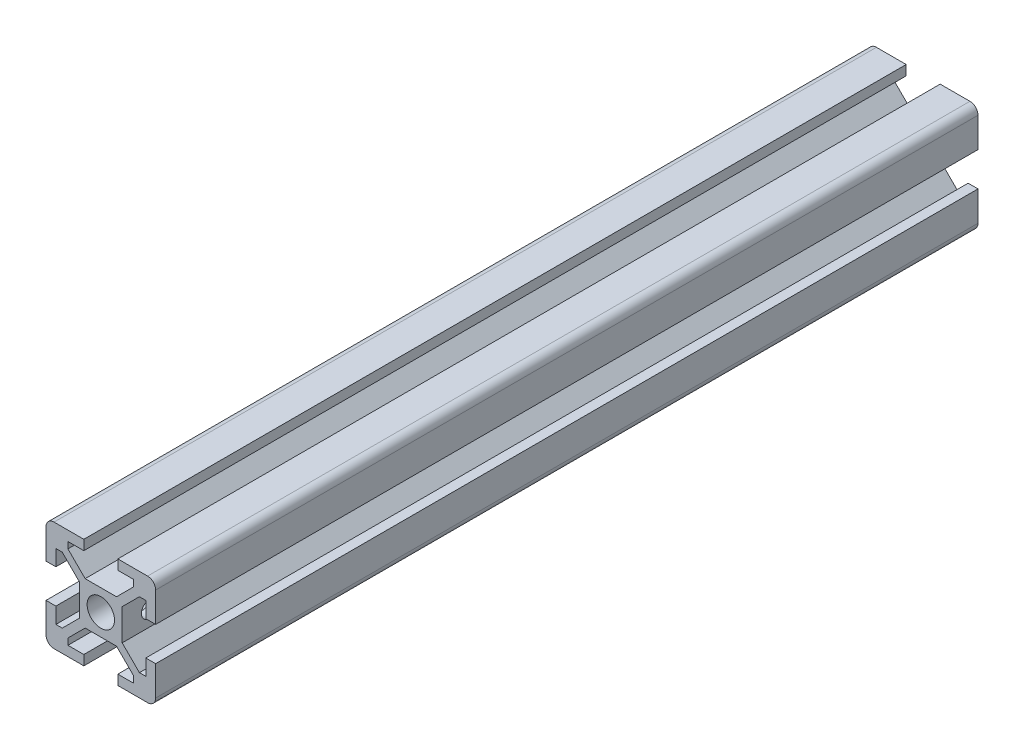
SolidWorks part; units mm, degrees
ref_plane "Front Plane" through (0, 0, 0) normal (0, 0, 1) x (1, 0, 0)
ref_plane "Top Plane" through (0, 0, 0) normal (0, 1, 0) x (1, 0, 0)
ref_plane "Right Plane" through (0, 0, 0) normal (1, 0, 0) x (0, 0, -1)
sketch "Sketch1" plane through (0, 0, 0) normal (0, 0, 1) x (1, 0, 0)
  line L0 (2.8606, 3.9) -> (6, 7.0394)
  line L5 (0, 3.9) -> (2.8606, 3.9)
  line L8 (3.9, 2.8606) -> (3.9, 0)
  line L9 (3.9, 0) -> (3.9, -2.8606)
  line L10 (3.9, -2.8606) -> (7.0394, -6)
  line L11 (6, 7.0394) -> (6, 8.2)
  line L12 (6, 8.2) -> (3.1, 8.2)
  line L13 (3.1, 8.2) -> (3.1, 10)
  line L14 (3.1, 10) -> (10, 10)
  line L15 (10, 10) -> (10, 3.1)
  line L16 (10, 3.1) -> (8.2, 3.1)
  line L17 (8.2, 3.1) -> (8.2, 6)
  line L18 (8.2, 6) -> (7.0394, 6)
  line L19 (7.0394, 6) -> (3.9, 2.8606)
  line L22 (7.0394, -6) -> (8.2, -6)
  line L23 (8.2, -6) -> (8.2, -3.1)
  line L24 (8.2, -3.1) -> (10, -3.1)
  line L25 (10, -3.1) -> (10, -10)
  line L26 (10, -10) -> (3.1, -10)
  line L27 (3.1, -10) -> (3.1, -8.2)
  line L28 (3.1, -8.2) -> (6, -8.2)
  line L29 (6, -8.2) -> (6, -7.0394)
  line L30 (6, -7.0394) -> (2.8606, -3.9)
  line L31 (2.8606, -3.9) -> (0, -3.9)
  line L32 (0, -3.9) -> (-2.8606, -3.9)
  line L33 (-2.8606, -3.9) -> (-6, -7.0394)
  line L34 (-6, -7.0394) -> (-6, -8.2)
  line L35 (-6, -8.2) -> (-3.1, -8.2)
  line L36 (-3.1, -8.2) -> (-3.1, -10)
  line L37 (-3.1, -10) -> (-10, -10)
  line L38 (-10, -10) -> (-10, -3.1)
  line L39 (-10, -3.1) -> (-8.2, -3.1)
  line L40 (-8.2, -3.1) -> (-8.2, -6)
  line L41 (-8.2, -6) -> (-7.0394, -6)
  line L42 (-7.0394, -6) -> (-3.9, -2.8606)
  line L43 (-3.9, -2.8606) -> (-3.9, 0)
  line L44 (-3.9, 0) -> (-3.9, 2.8606)
  line L45 (-3.9, 2.8606) -> (-7.0394, 6)
  line L46 (-7.0394, 6) -> (-8.2, 6)
  line L47 (-8.2, 6) -> (-8.2, 3.1)
  line L48 (-8.2, 3.1) -> (-10, 3.1)
  line L49 (-10, 3.1) -> (-10, 10)
  line L50 (-10, 10) -> (-3.1, 10)
  line L51 (-3.1, 10) -> (-3.1, 8.2)
  line L52 (-3.1, 8.2) -> (-6, 8.2)
  line L53 (-6, 8.2) -> (-6, 7.0394)
  line L54 (-6, 7.0394) -> (-2.8606, 3.9)
  line L55 (-2.8606, 3.9) -> (0, 3.9)
  circle A0 centre (0, 0) radius 2.5
  point P0 (0, 0)
  dimension "D9" = 5
  dimension "D1" = 45
  dimension "D2" = 10
  dimension "D3" = 6.1
  dimension "D4" = 3.1
  dimension "D5" = 1.47
  dimension "D6" = 4.3
  dimension "D7" = 6
  dimension "D8" = 4
extrude "Boss-Extrude1" add sketch "Sketch1" along normal blind 150
fillet "Fillet1" radius 1.47 4 edges at (-10, -10, 75) (-10, 10, 75) (10, -10, 75) (10, 10, 75)
sketch "Sketch2" plane through (-3.9, 0, 0) normal (-1, 0, 0) x (0, 0, 1)
  line L0 (150, 2.8606) -> (150, -2.8606) construction
  line L2 (0, 2.8606) -> (0, -2.8606) construction
  circle A0 centre (145, 0) radius 1.5
  circle A1 centre (135, 0) radius 1.5
  circle A2 centre (125, 0) radius 1.5
  circle A3 centre (30, 0) radius 1.5
  point P12 (0, 0)
  dimension "D1" = 3
  dimension "D4" = 3
  dimension "D2" = 5
  dimension "D5" = 30
  dimension "D3" = 3
extrude "Cut-Extrude1" cut sketch "Sketch2" against normal through all
sketch "Sketch3" plane through (0, 3.9, 0) normal (0, 1, 0) x (1, 0, 0)
  line L0 (2.8606, 0) -> (-2.8606, 0) construction
  circle A0 centre (0, -30) radius 1.5
  dimension "D1" = 3
  dimension "D2" = 30
extrude "Cut-Extrude2" cut sketch "Sketch3" against normal through all
